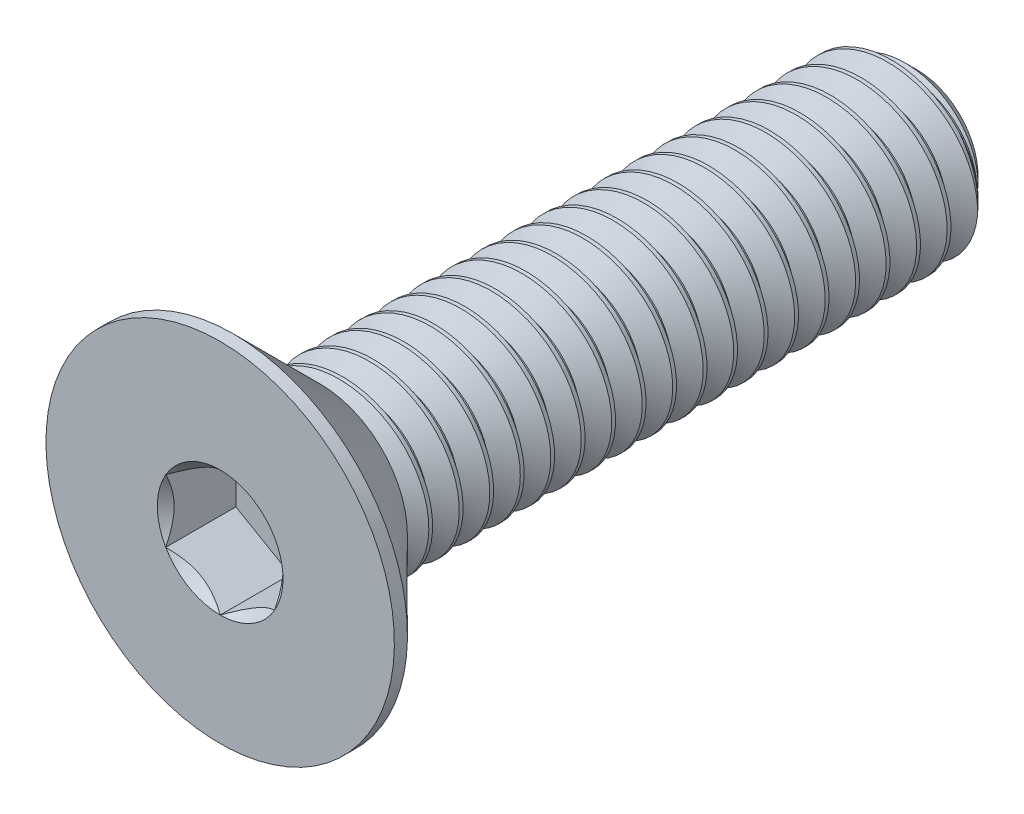
SolidWorks part; units mm, degrees
ref_plane "Front" through (0, 0, 0) normal (0, 0, 1) x (1, 0, 0)
ref_plane "Top" through (0, 0, 0) normal (0, 1, 0) x (1, 0, 0)
ref_plane "Right" through (0, 0, 0) normal (1, 0, 0) x (0, 0, -1)
sketch "Sketch1" plane through (0, 0, 0) normal (1, 0, 0) x (0, 0, -1)
  line L0 (-8, 4) -> (-7.7, 4) construction
  line L1 (-7.7, 4) -> (-5.7, 2) construction
  line L2 (-8, 2) -> (8, 2) construction
  line L3 (8, 2) -> (8, 0) construction
  line L4 (8, 0) -> (-8, 0) construction
  line L5 (-8, 0) -> (-8, 4) construction
  line L6 (-8, 4) -> (-8, -4) construction
  line L7 (8, 2) -> (8, -2) construction
  line L8 (-8, -4) -> (-7.7, -4) construction
  line L9 (-7.7, -4) -> (-5.7, -2) construction
  line L11 (-8, 2) -> (-8, 0) construction
  line L12 (-5.7, 2) -> (-5.7, 0) construction
  line L13 (7.9562, 2.0758) -> (8.3063, 1.4696) construction
  line L14 (8.3063, 1.4696) -> (8.6562, 2.0758) construction
  line L15 (8.6562, 2.0758) -> (7.9562, 2.0758) construction
  line L16 (8.3063, 2.0758) -> (8.3063, 2) construction
  line L17 (8.3063, 2) -> (8.3063, 1.5453) construction
  line L18 (8.3063, 1.5453) -> (8.3063, 1.4696) construction
  line L19 (8.3063, 2.0379) -> (8.6344, 2.0379) construction
  line L20 (8.3063, 2.0379) -> (7.9781, 2.0379) construction
  line L21 (8, 2) -> (8.6125, 2) construction
  line L22 (8.2625, 1.5453) -> (8.35, 1.5453) construction
  line L23 (8, -2) -> (-5.7, -2) construction
  point P10 (6.25, -2)
  point P24 (-5.7, 2)
  point P30 (0, 0)
  dimension "Head Diameter" = 8
  dimension "Head Height" = 2.3
  dimension "Length" = 16
  dimension "Countersink Angle" = 90
  dimension "Thread Pitch" = 0.7
  dimension "D2" = 0.0875
  dimension "Minimum Thread Length" = 13.7
  dimension "Thread Size" = 4
  dimension "D1" = 1.75
sketch "Sketch2" plane through (0, 0, 0) normal (0, 0, 1) x (1, 0, 0)
  line L1 (0, 1.4434) -> (-1.25, 0.7217) construction
  line L2 (-1.25, 0.7217) -> (-1.25, -0.7217) construction
  line L3 (-1.25, -0.7217) -> (0, -1.4434) construction
  line L4 (0, -1.4434) -> (1.25, -0.7217) construction
  line L5 (1.25, -0.7217) -> (1.25, 0.7217) construction
  line L6 (1.25, 0.7217) -> (0, 1.4434) construction
  circle A0 centre (0, 0) radius 1.25 construction
  dimension "Drive Size" = 2.5
sketch "Sketch3" plane through (0, 0, 0) normal (1, 0, 0) x (0, 0, -1)
  line L0 (-8, 2) -> (8, 2)
  line L1 (8, 2) -> (8, 0)
  line L2 (8, 0) -> (-8, 0)
  line L3 (-8, 0) -> (-8, 2)
revolve "Revolve1" add sketch "Sketch3" angle 360 about L4
chamfer "Chamfer1" distance 0.6 angle 45 1 edges at (0, 2, -8)
sketch "Sketch6" plane through (0, 0, 0) normal (1, 0, 0) x (0, 0, -1)
  line L0 (-8, 4) -> (-7.7, 4)
  line L1 (-7.7, 4) -> (-5.7, 2)
  line L2 (-5.7, 2) -> (-5.7, 0)
  line L3 (-5.7, 0) -> (-8, 0)
  line L4 (-8, 0) -> (-8, 4)
revolve "Revolve2" add sketch "Sketch6" angle 360 about L4
sketch "Sketch8" plane through (0, 0, 8) normal (0, 0, 1) x (1, 0, 0)
  line L0 (0, 1.4434) -> (-1.25, 0.7217) construction
  line L1 (1.25, 0.7217) -> (0, 1.4434) construction
  line L2 (1.25, -0.7217) -> (1.25, 0.7217) construction
  line L3 (0, -1.4434) -> (1.25, -0.7217) construction
  line L4 (-1.25, 0.7217) -> (-1.25, -0.7217) construction
  line L5 (-1.25, -0.7217) -> (0, -1.4434) construction
  line L6 (0, 1.4434) -> (-1.25, 0.7217)
  line L7 (1.25, 0.7217) -> (0, 1.4434)
  line L8 (1.25, -0.7217) -> (1.25, 0.7217)
  line L9 (0, -1.4434) -> (1.25, -0.7217)
  line L10 (-1.25, 0.7217) -> (-1.25, -0.7217)
  line L11 (-1.25, -0.7217) -> (0, -1.4434)
extrude "Cut-Extrude1" cut sketch "Sketch8" against normal blind 1.61
sketch "Sketch9" plane through (0, 0, 8) normal (0, 0, 1) x (1, 0, 0)
  circle A0 centre (0, 0) radius 1.4434
extrude "Cut-Extrude2" cut sketch "Sketch9" against normal up to next (1.61 mm away) draft 45
ref_plane "Plane1" through (0, 0, 5.7) normal (0, 0, 1) x (1, 0, 0)
split "Split1" trim tools "Plane1" bodies to split 124 resulting bodies 126 127
sketch "Sketch4" plane through (0, 0, -8) normal (0, 0, -1) x (-1, 0, 0)
  circle A0 centre (0, 0) radius 2 construction
  circle A1 centre (0, 0) radius 2
curve "Helix/Spiral1" pitch 0.7 height 14.4 turns 20.5714
sketch "Sketch10" plane through (0, 0, 0) normal (1, 0, 0) x (0, 0, -1)
  line L0 (7.9781, 2.0379) -> (8.6344, 2.0379)
  line L1 (8.6344, 2.0379) -> (8.35, 1.5453)
  line L2 (8.35, 1.5453) -> (8.2625, 1.5453)
  line L3 (8.2625, 1.5453) -> (7.9781, 2.0379)
sweep "Cut-Sweep1" cut profiles "Sketch10" path "Helix/Spiral1"
equation "\"D2@Sketch1\" = \"Thread Pitch@Sketch1\" / 8"
equation "\"D4@Helix/Spiral1\"=\"Thread Pitch@Sketch1\""
equation "\"D3@Helix/Spiral1\"=\"Minimum Thread Length@Sketch1\"+\"Thread Pitch@Sketch1\""
equation "\"D1@Chamfer1\"=\"Thread Size@Sketch1\"*.15"
equation "\"D1@Cut-Extrude1\"=\"Head Height@Sketch1\"*.7"
equation "\"D1@Sketch1\"=\"Thread Pitch@Sketch1\"*2.5"
